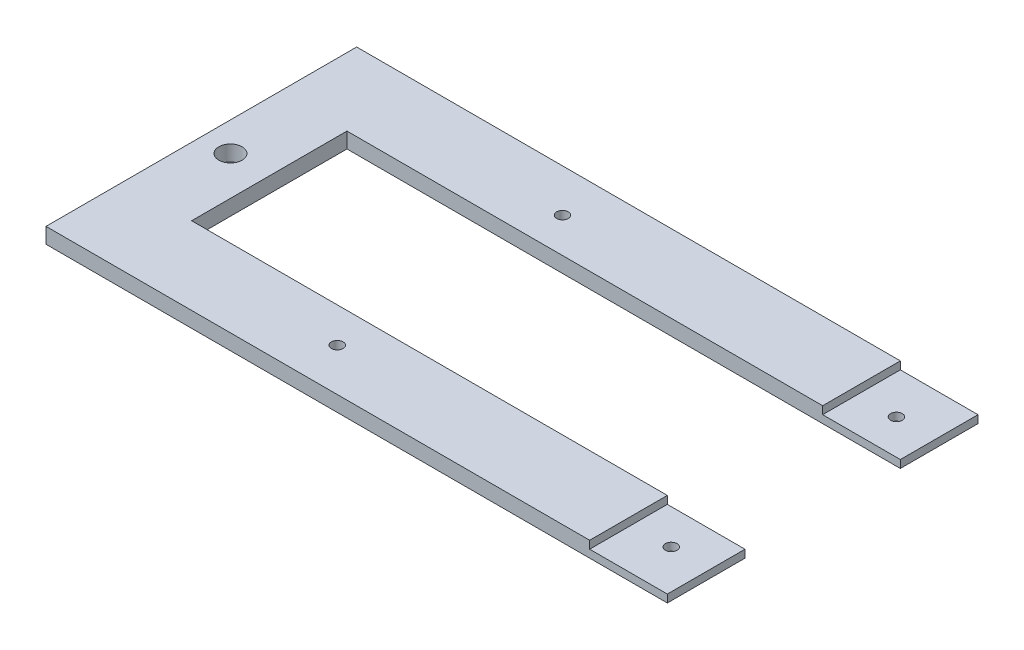
SolidWorks part; units mm, degrees
ref_plane "Front Plane" through (0, 0, 0) normal (0, 0, 1) x (1, 0, 0)
ref_plane "Top Plane" through (0, 0, 0) normal (0, 1, 0) x (1, 0, 0)
ref_plane "Right Plane" through (0, 0, 0) normal (1, 0, 0) x (0, 0, -1)
sketch "Sketch1" plane through (0, 0, 0) normal (0, 1, 0) x (1, 0, 0)
  line L0 (0, -40) -> (0, 40)
  line L1 (0, 40) -> (160, 40)
  line L2 (160, 40) -> (160, 20)
  line L3 (-190.8824, 0) -> (429.1176, 0) construction
  line L4 (160, 20) -> (17.5, 20)
  line L5 (17.5, 20) -> (17.5, -20)
  line L6 (17.5, 0) -> (0, 0)
  line L7 (160, -20) -> (17.5, -20)
  line L8 (160, -40) -> (160, -20)
  line L9 (0, -40) -> (160, -40)
  circle A0 centre (7.5, 0) radius 3
  circle A1 centre (64, 29) radius 1.5
  circle A2 centre (150, 29) radius 1.5
  circle A3 centre (150, -29) radius 1.5
  circle A4 centre (64, -29) radius 1.5
  dimension "D5" = 0
  dimension "D6" = 6
  dimension "D7" = 3
  dimension "D8" = 3
  dimension "D9" = 86
  dimension "D10" = 29
  dimension "D11" = 10
  dimension "D13" = 29
  dimension "D1" = 40
  dimension "D2" = 17.5
  dimension "D3" = 20
  dimension "D4" = 160
  dimension "D12" = 7.5
extrude "Boss-Extrude1" add sketch "Sketch1" along normal blind 4 contours A0 L6 L0 L9 L8 L7 L5 A3 A4 | A0 L6 L5 L4 L2 L1 L0 A2 A1
sketch "Sketch2" plane through (160, 0, 0) normal (1, 0, 0) x (0, 0, -1)
  line L0 (40, 4) -> (40, 0) construction
  line L1 (20, 4) -> (40, 4)
  line L2 (20, 4) -> (20, 2)
  line L3 (20, 2) -> (40, 2)
  line L4 (40, 4) -> (40, 2)
  line L5 (0, 0) -> (0, 24.9083) construction
  line L6 (-20, 2) -> (-40, 2)
  line L7 (-40, 4) -> (-40, 2)
  line L8 (-20, 4) -> (-40, 4)
  line L9 (-20, 4) -> (-20, 2)
extrude "Cut-Extrude1" cut sketch "Sketch2" against normal blind 20
